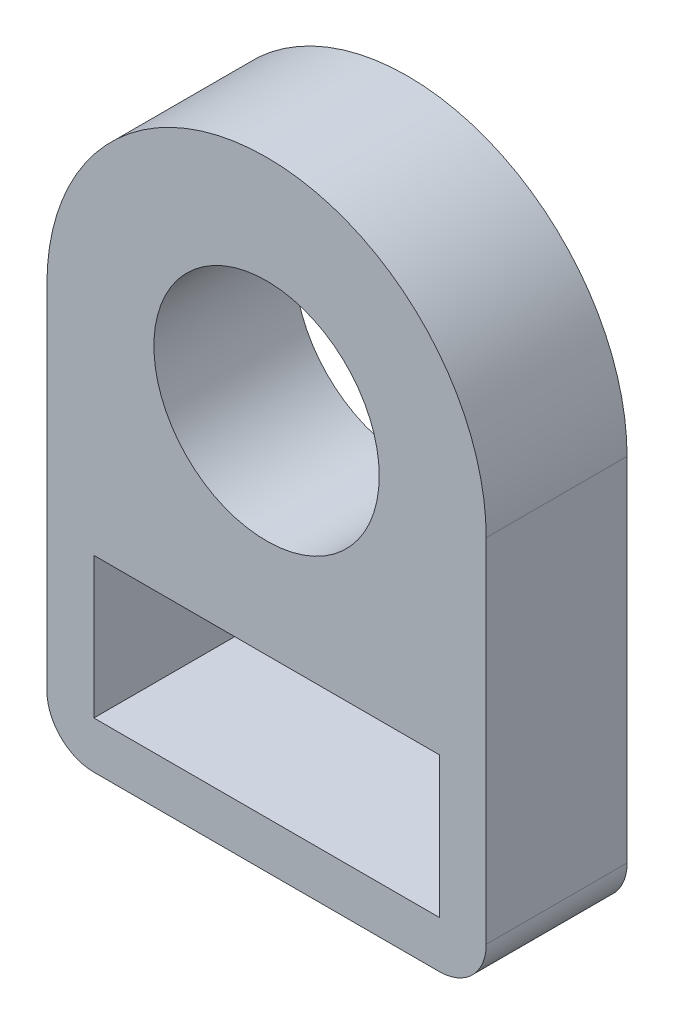
SolidWorks part; units mm, degrees
ref_plane "Plano frontal" through (0, 0, 0) normal (0, 0, 1) x (1, 0, 0)
ref_plane "Plano superior" through (0, 0, 0) normal (0, 1, 0) x (1, 0, 0)
ref_plane "Plano direito" through (0, 0, 0) normal (1, 0, 0) x (0, 0, -1)
sketch "Sketch1" plane through (0, 0, 0) normal (0, 0, 1) x (1, 0, 0)
  line L0 (-18.39, -12.5) -> (18.3904, -12.5)
  line L1 (-18.39, 7.5) -> (18.39, 7.5)
  line L2 (-18.39, 7.5) -> (-18.39, -7.5)
  line L3 (-18.39, -7.5) -> (18.39, -7.5)
  line L4 (18.39, 7.5) -> (18.39, -7.5)
  line L5 (-18.39, 7.5) -> (18.39, -7.5) construction
  line L6 (-18.39, -7.5) -> (18.39, 7.5) construction
  line L10 (-23.39, 12.5) -> (23.39, 12.5) construction
  line L11 (-23.39, -12.5) -> (23.39, -12.5) construction
  line L12 (-23.39, 12.5) -> (-23.39, -12.5) construction
  line L13 (23.39, 12.5) -> (23.39, -12.5) construction
  line L14 (-23.39, -7.5) -> (-23.39, 30.02)
  line L17 (23.3903, -7.48) -> (23.3903, 30.02)
  circle A2 centre (0, 30.02) radius 12
  arc A4 (-18.39, -12.5) -> (-23.39, -7.5) centre (-18.39, -7.5) cw
  arc A5 (18.3904, -12.5) -> (23.3903, -7.48) centre (18.3904, -7.5) ccw
  arc A6 (-23.39, 30.02) -> (23.3903, 30.02) centre (0.0002, 30.02) cw
  point P0 (0, 0)
  point P10 (0, 7.5)
  dimension "D5" = 24
  dimension "D1" = 36.78
  dimension "D2" = 15
  dimension "D4" = 22.52
  dimension "D3" = 5
extrude "Boss-Extrude1" add sketch "Sketch1" along normal blind 15
